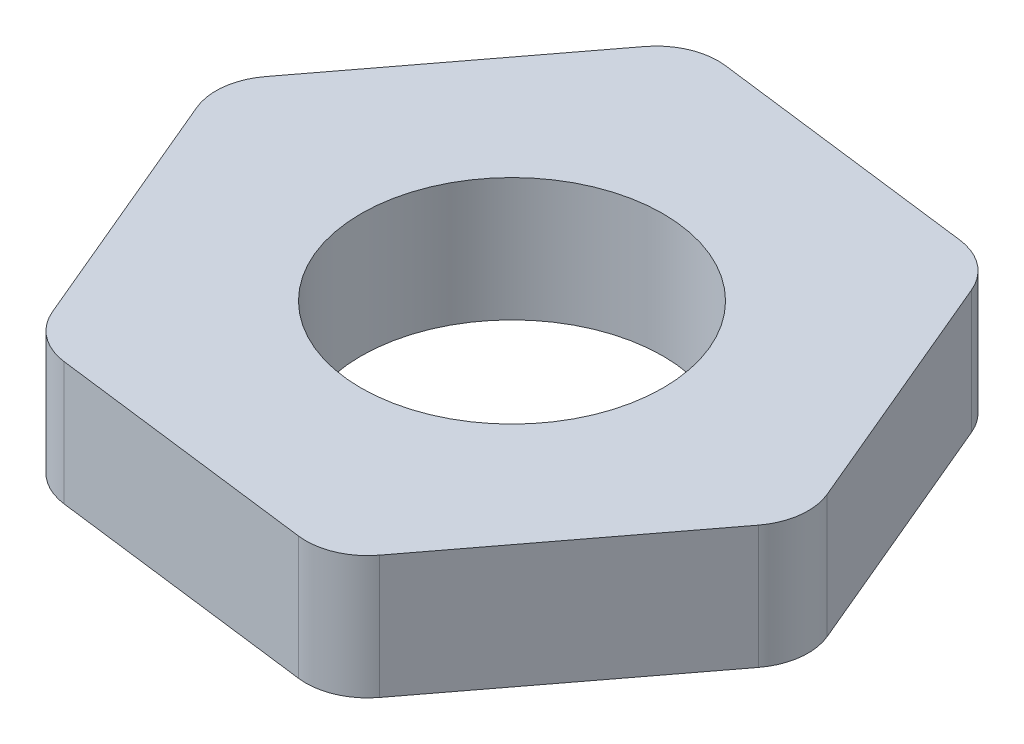
SolidWorks part; units mm, degrees
material "Plain Carbon Steel"
ref_plane "Front" through (0, 0, 0) normal (0, 0, 1) x (1, 0, 0)
ref_plane "Top" through (0, 0, 0) normal (0, 1, 0) x (1, 0, 0)
ref_plane "Right" through (0, 0, 0) normal (1, 0, 0) x (0, 0, -1)
sketch "Sketch1" plane through (0, 0, 0) normal (0, 1, 0) x (1, 0, 0)
  line L1 (-1.0745, 2.5545) -> (-2.7495, 0.3467)
  line L2 (-2.7495, 0.3467) -> (-1.675, -2.2078)
  line L3 (-1.675, -2.2078) -> (1.0745, -2.5545)
  line L4 (1.0745, -2.5545) -> (2.7495, -0.3467)
  line L5 (2.7495, -0.3467) -> (1.675, 2.2078)
  line L6 (1.675, 2.2078) -> (-1.0745, 2.5545)
  circle A0 centre (0, 0) radius 1.225
  circle A1 centre (0, 0) radius 2.4 construction
  dimension "D1" = 2.45
  dimension "D2" = 4.8
  dimension "D3" = 1.675
extrude "Boss-Extrude1" add sketch "Sketch1" along normal blind 1
fillet "Fillet1" radius 0.5 6 edges at (-1.0745, 0.5, -2.5545) (-2.7495, 0.5, -0.3467) (-1.675, 0.5, 2.2078) (1.0745, 0.5, 2.5545) (2.7495, 0.5, 0.3467) (1.675, 0.5, -2.2078)
